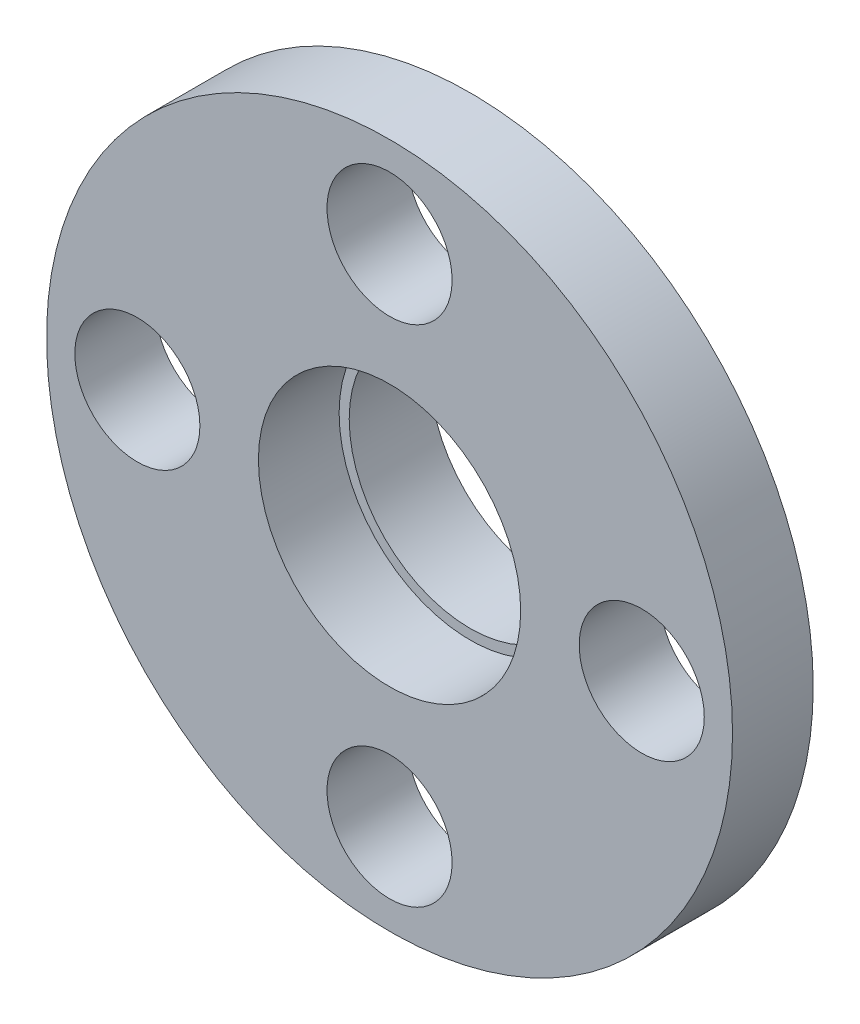
SolidWorks part; units mm, degrees
ref_plane "前视基准面" through (0, 0, 0) normal (0, 0, 1) x (1, 0, 0)
ref_plane "上视基准面" through (0, 0, 0) normal (0, 1, 0) x (1, 0, 0)
ref_plane "右视基准面" through (0, 0, 0) normal (1, 0, 0) x (0, 0, -1)
sketch "草图1" plane through (0, 0, 0) normal (0, 0, 1) x (1, 0, 0)
  circle A0 centre (0, 0) radius 3.25
  circle A1 centre (0, 0) radius 3
  dimension "D1" = 6.5
  dimension "D2" = 6.5
  dimension "D3" = 6
extrude "凸台-拉伸3" add sketch "草图1" along normal blind 2
sketch "草图3" plane through (0, 0, 2) normal (0, 0, 1) x (1, 0, 0)
  circle A0 centre (0, 0) radius 8.5
  circle A1 centre (0, 0) radius 6.25
  circle A2 centre (0, 6.25) radius 1.55
  circle A3 centre (6.25, 0) radius 1.55
  circle A4 centre (0, -6.25) radius 1.55
  circle A5 centre (-6.25, 0) radius 1.55
  point P15 (0, 0)
  circle M1 centre (0, 0) radius 3.25
  dimension "D1" = 17
  dimension "D2" = 12.5
  dimension "D3" = 3.1
  dimension "D4" = 4
extrude "凸台-拉伸4" add sketch "草图3" along normal blind 2 separate body contours A0 A5 A1 A2 A3 A4 | A5 A1 A4 A3 A2 M1
sketch "草图4" plane through (0, 0, 4) normal (0, 0, 1) x (1, 0, 0)
  circle A0 centre (0, 0) radius 8.5
  dimension "D1" = 17
